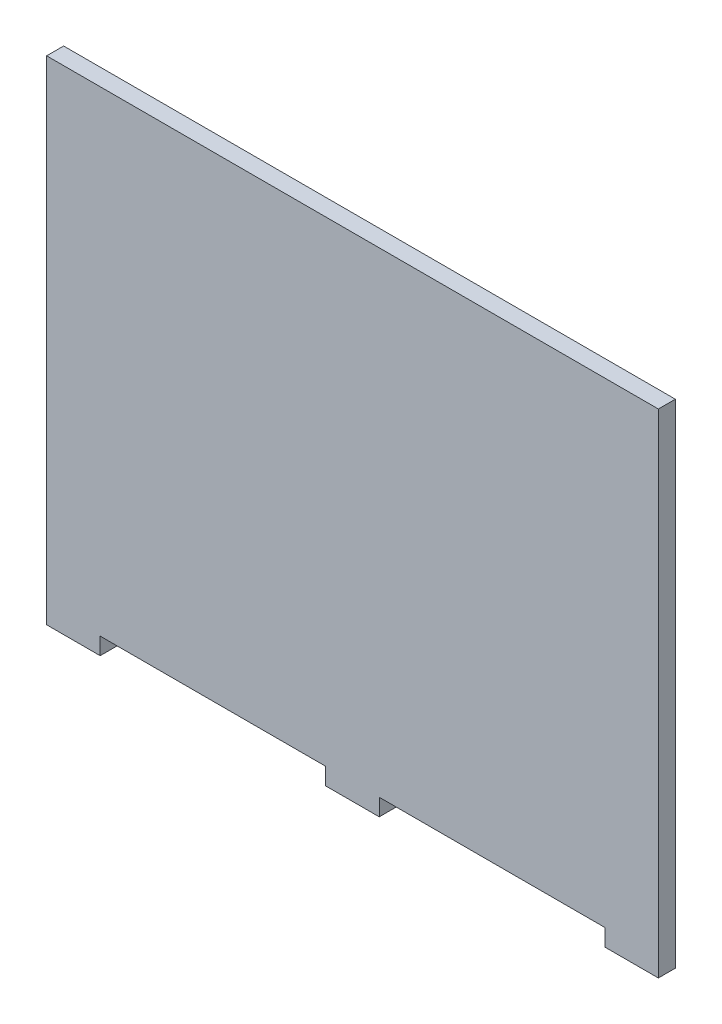
SolidWorks part; units mm, degrees
ref_plane "Front Plane" through (0, 0, 0) normal (0, 0, 1) x (1, 0, 0)
ref_plane "Top Plane" through (0, 0, 0) normal (0, 1, 0) x (1, 0, 0)
ref_plane "Right Plane" through (0, 0, 0) normal (1, 0, 0) x (0, 0, -1)
sketch "Sketch1" plane through (0, 0, 0) normal (0, 0, 1) x (1, 0, 0)
  line L0 (94.3, -6.35) -> (114.3, -6.35) construction
  line L1 (114.3, -6.35) -> (114.3, 0) construction
  line L3 (94.3, 0) -> (94.3, -6.35) construction
  line L4 (10, -6.35) -> (94.3, -6.35) construction
  line L5 (94.3, -6.35) -> (94.3, 0) construction
  line L6 (94.3, 0) -> (10, 0) construction
  line L7 (10, 0) -> (10, -6.35) construction
  line L8 (-10, -6.35) -> (10, -6.35) construction
  line L9 (10, -6.35) -> (10, 0) construction
  line L11 (-10, 0) -> (-10, -6.35) construction
  line L12 (-94.3, -6.35) -> (-10, -6.35) construction
  line L13 (-10, -6.35) -> (-10, 0) construction
  line L14 (-10, 0) -> (-94.3, 0) construction
  line L15 (-94.3, 0) -> (-94.3, -6.35) construction
  line L16 (94.3, -6.35) -> (114.3, -6.35)
  line L17 (114.3, -6.35) -> (114.3, 0)
  line L19 (94.3, 0) -> (94.3, -6.35)
  line L20 (10, -6.35) -> (94.3, -6.35)
  line L21 (94.3, -6.35) -> (94.3, 0)
  line L22 (94.3, 0) -> (10, 0)
  line L23 (10, 0) -> (10, -6.35)
  line L24 (-10, -6.35) -> (10, -6.35)
  line L25 (10, -6.35) -> (10, 0)
  line L27 (-10, 0) -> (-10, -6.35)
  line L28 (-94.3, -6.35) -> (-10, -6.35)
  line L29 (-10, -6.35) -> (-10, 0)
  line L30 (-10, 0) -> (-94.3, 0)
  line L31 (-94.3, 0) -> (-94.3, -6.35)
  line L32 (10, 0) -> (94.3, 0)
  line L33 (-94.3, 0) -> (-10, 0)
  line L34 (-114.3, 0) -> (-114.3, 177.8)
  line L35 (-114.3, 177.8) -> (114.3, 177.8)
  line L36 (-114.3, -6.35) -> (-94.3, -6.35)
  line L37 (-94.3, -6.35) -> (-94.3, 0)
  line L38 (-94.3, 0) -> (-114.3, 0)
  line L39 (-114.3, 0) -> (-114.3, -6.35)
  line L40 (-114.3, -6.35) -> (-94.3, -6.35)
  line L41 (-94.3, -6.35) -> (-94.3, 0)
  line L43 (-114.3, 0) -> (-114.3, -6.35)
  line L44 (114.3, 0) -> (114.3, 177.8)
  dimension "D2" = 228.6
  dimension "D3" = 177.8
  dimension "D1" = 0
extrude "Boss-Extrude1" add sketch "Sketch1" against normal blind 6.35 contours L17 L44 L35 L34 L43 L40 L31 L30 L27 L24 L23 L22 L19 L16
